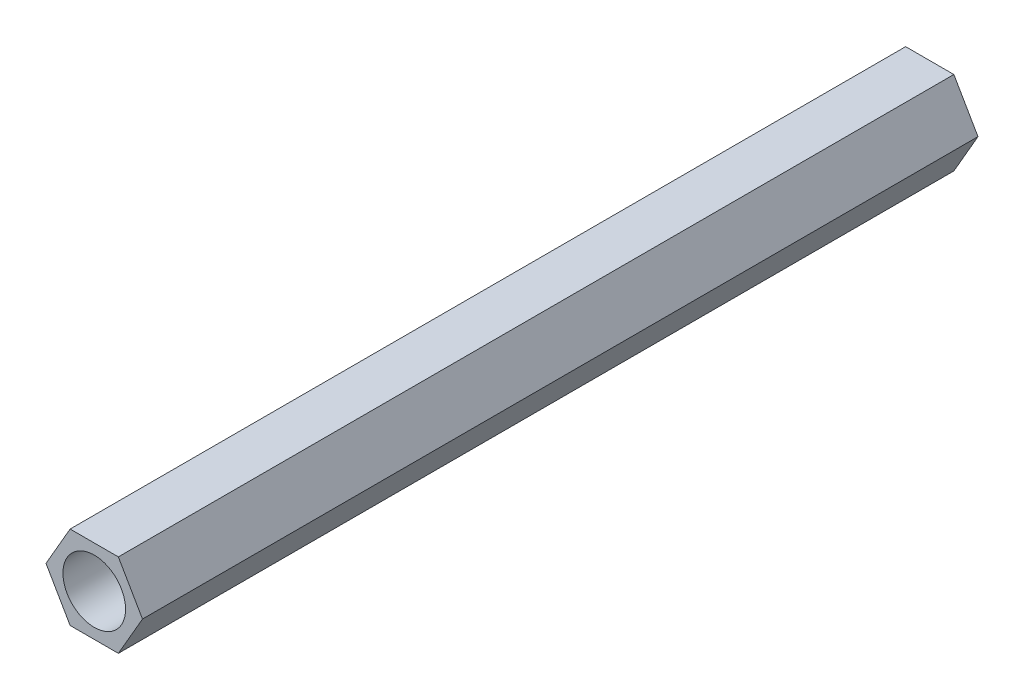
SolidWorks part; units mm, degrees
ref_plane "前视基准面" through (0, 0, 0) normal (0, 0, 1) x (1, 0, 0)
ref_plane "上视基准面" through (0, 0, 0) normal (0, 1, 0) x (1, 0, 0)
ref_plane "右视基准面" through (0, 0, 0) normal (1, 0, 0) x (0, 0, -1)
other "Configuration Table"
sketch "草图1" plane through (0, 0, 0) normal (0, 0, 1) x (1, 0, 0)
  line L1 (2.3094, 0) -> (1.1547, 2)
  line L2 (1.1547, 2) -> (-1.1547, 2)
  line L3 (-1.1547, 2) -> (-2.3094, 0)
  line L4 (-2.3094, 0) -> (-1.1547, -2)
  line L5 (-1.1547, -2) -> (1.1547, -2)
  line L6 (1.1547, -2) -> (2.3094, 0)
  circle A0 centre (0, 0) radius 2 construction
  circle A1 centre (0, 0) radius 1.5
  dimension "D1" = 2
extrude "凸台-拉伸1" add sketch "草图1" along normal blind 40
